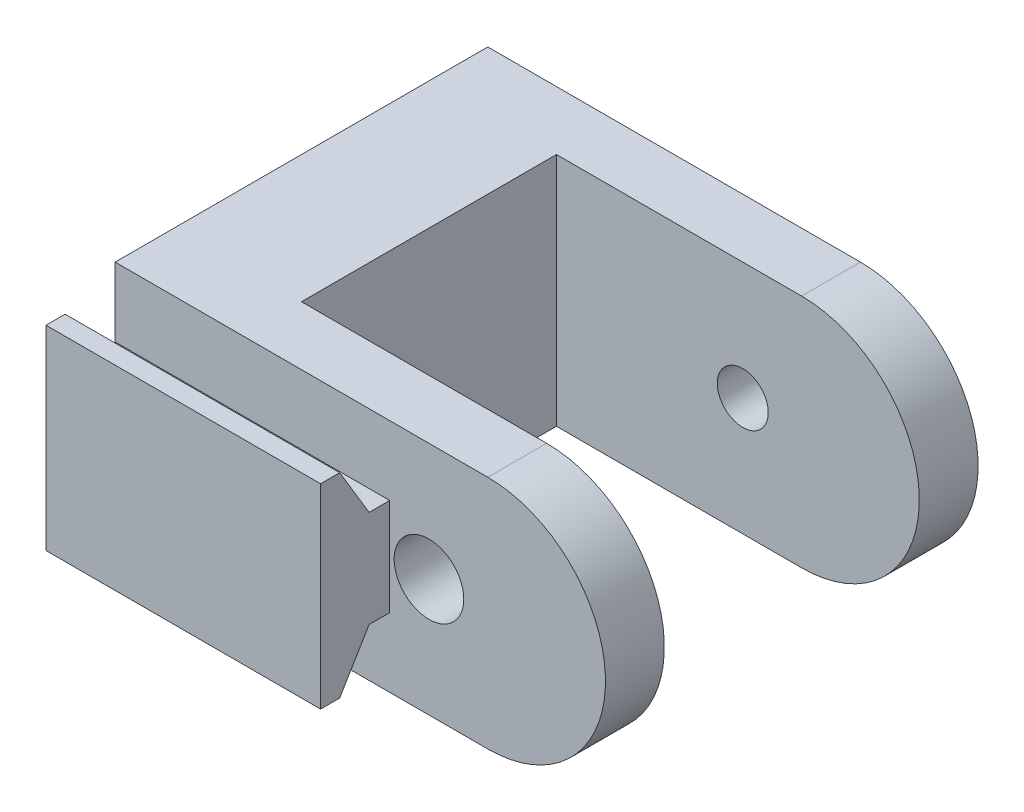
SolidWorks part; units mm, degrees
ref_plane "Front Plane" through (0, 0, 0) normal (0, 0, 1) x (1, 0, 0)
ref_plane "Top Plane" through (0, 0, 0) normal (0, 1, 0) x (1, 0, 0)
ref_plane "Right Plane" through (0, 0, 0) normal (1, 0, 0) x (0, 0, -1)
sketch "Sketch1" plane through (0, 0, 0) normal (0, 1, 0) x (1, 0, 0)
  line L0 (0, 0) -> (50, 0)
  line L1 (50, 0) -> (50, 6)
  line L2 (50, 6) -> (13, 6)
  line L3 (13, 6) -> (13, 32)
  line L4 (13, 32) -> (50, 32)
  line L5 (50, 32) -> (50, 38)
  line L6 (50, 38) -> (0, 38)
  line L7 (0, 38) -> (0, 0)
  dimension "D1" = 6
  dimension "D2" = 6
  dimension "D3" = 26
  dimension "D4" = 13
  dimension "D5" = 50
  dimension "D6" = 50
extrude "Boss-Extrude1" add sketch "Sketch1" along normal blind 24
sketch "Sketch3" plane through (0, 0, -38) normal (0, 0, -1) x (-1, 0, 0)
  line L0 (-50, 12) -> (0, 12) construction
  line L1 (-50, 24) -> (0, 24)
  line L2 (-50, 24) -> (-50, 0)
  line L3 (-50, 0) -> (0, 0)
  line L4 (0, 24) -> (0, 0)
  line L5 (-38, 24) -> (-50, 24)
  line L6 (-50, 12) -> (-50, 0)
  line L7 (-50, 0) -> (-38, 0)
  line L8 (-50, 12) -> (-50, 24)
  arc A0 (-50, 12) -> (-38, 0) centre (-38, 12) ccw
  arc A1 (-50, 12) -> (-38, 24) centre (-38, 12) cw
  circle A2 centre (-32, 12) radius 2.6
  point P8 (-38, 12)
  point P12 (-32, 12)
  line M5 (-50, 0) -> (0, 0)
  line M8 (-50, 24) -> (-50, 0)
  dimension "D3" = 5.2
  dimension "D1" = 12
  dimension "D2" = 18
extrude "Cut-Extrude1" cut sketch "Sketch3" against normal blind 60 contours A1 L1 M8 | A0 L2 M5 | A2
sketch "Sketch5" plane through (0, 0, 0) normal (0, 0, 1) x (1, 0, 0)
  circle A0 centre (32, 12) radius 3.55
  dimension "D1" = 7.1
extrude "Cut-Extrude2" cut sketch "Sketch5" against normal blind 10
sketch "Sketch7" plane through (0, 0, 0) normal (-1, 0, 0) x (0, 0, 1)
  line L0 (-38, 12) -> (18.2624, 12) construction
  line L1 (-38, 24) -> (-38, 0) construction
  line L2 (0, 16.95) -> (2.1, 16.95)
  line L4 (0, 24) -> (0, 0) construction
  line L5 (2.1, 16.95) -> (5.1, 21.95)
  line L6 (5.1, 21.95) -> (7.05, 21.95)
  line L7 (7.05, 21.95) -> (7.05, 2.05)
  line L8 (0, 16.95) -> (0, 7.05)
  line L9 (5.1, 2.05) -> (7.05, 2.05)
  line L10 (2.1, 7.05) -> (5.1, 2.05)
  line L11 (0, 7.05) -> (2.1, 7.05)
  point P14 (0, 12)
  point P15 (7.05, 12)
  dimension "D1" = 4.95
  dimension "D2" = 2.1
  dimension "D3" = 4.95
  dimension "D4" = 1.95
  dimension "D5" = 9.95
extrude "Boss-Extrude2" add sketch "Sketch7" against normal blind 28
